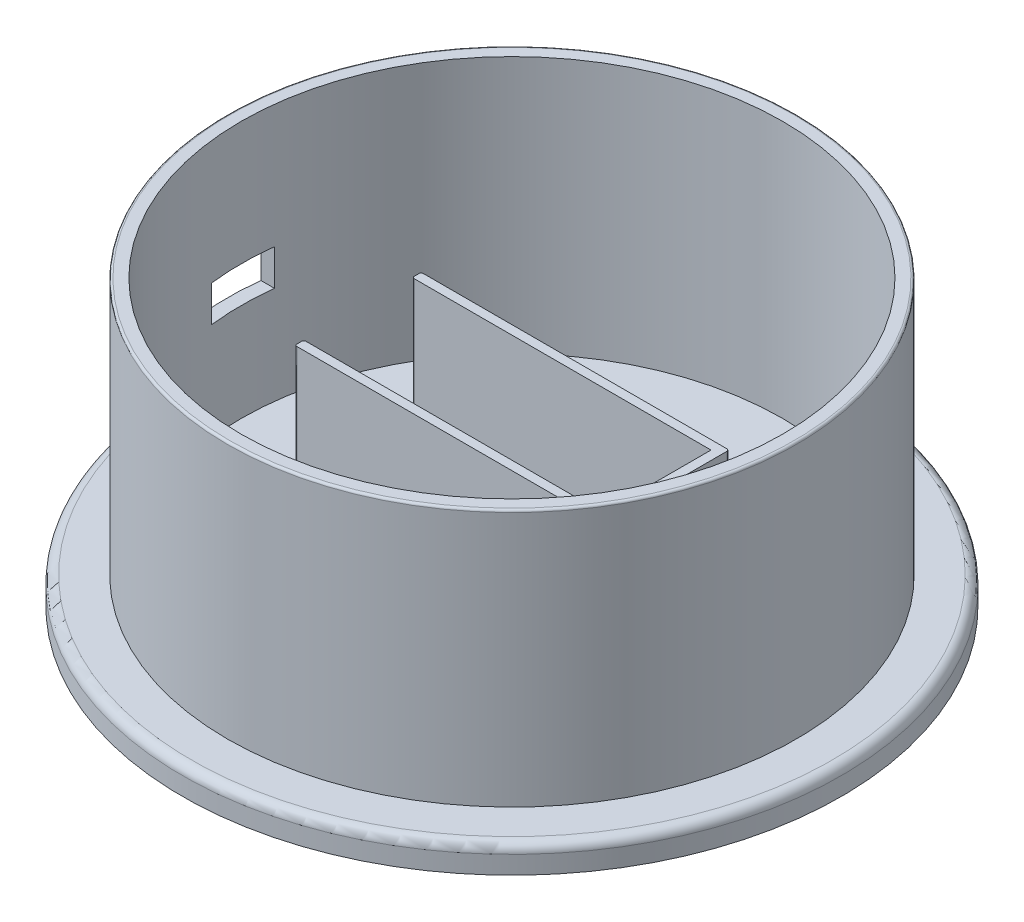
SolidWorks part; units mm, degrees
ref_plane "Front Plane" through (0, 0, 0) normal (0, 0, 1) x (1, 0, 0)
ref_plane "Top Plane" through (0, 0, 0) normal (0, 1, 0) x (1, 0, 0)
ref_plane "Right Plane" through (0, 0, 0) normal (1, 0, 0) x (0, 0, -1)
other "Configuration Table"
sketch "Sketch1" plane through (0, 0, 0) normal (0, 1, 0) x (1, 0, 0)
  circle A0 centre (0, 0) radius 31.5
  circle A1 centre (0, 0) radius 30
  dimension "D1" = 63
  dimension "D2" = 60
extrude "Boss-Extrude1" add sketch "Sketch1" along normal blind 28.5
sketch "Sketch2" plane through (0, 0, 0) normal (0, -1, 0) x (1, 0, 0)
  circle A0 centre (0, 0) radius 36.5
  dimension "D1" = 73
extrude "Boss-Extrude2" add sketch "Sketch2" along normal blind 3
sketch "Sketch3" plane through (0, 0, 0) normal (0, 1, 0) x (1, 0, 0)
  line L0 (-16.05, 6) -> (-17.05, 6)
  line L1 (-16.05, 6) -> (16.05, 6)
  line L3 (-16.05, -6) -> (16.05, -6)
  line L4 (16.05, 6) -> (16.05, -6)
  line L5 (-17.05, 7) -> (17.05, 7)
  line L6 (-17.05, 7) -> (-17.05, 6)
  line L7 (-17.05, -7) -> (17.05, -7)
  line L8 (17.05, 7) -> (17.05, -7)
  line L9 (-16.05, -6) -> (-17.05, -6)
  line L10 (-17.05, -6) -> (-17.05, -7)
  circle A0 centre (0, 0) radius 30 construction
  dimension "D1" = 32.1
  dimension "D4" = 1
  dimension "D2" = 12
  dimension "D3" = 16.05
  dimension "D5" = 1
  dimension "D7" = 1
extrude "Boss-Extrude3" add sketch "Sketch3" along normal blind 17
sketch "Sketch4" plane through (16.05, 0, 0) normal (-1, 0, 0) x (0, 0, 1)
  line L0 (6, 17) -> (6, 0) construction
  line L1 (-3.5, 14.8357) -> (3.5, 14.8357)
  line L2 (-3.5, 14.8357) -> (-3.5, 10.8357)
  line L3 (-3.5, 10.8357) -> (3.5, 10.8357)
  line L4 (3.5, 14.8357) -> (3.5, 10.8357)
  dimension "D1" = 7
  dimension "D2" = 4
  dimension "D3" = 2.5
extrude "Cut-Extrude1" cut sketch "Sketch4" along normal through all
fillet "Fillet1" radius 1 1 edges at (0, 0, -36.5)
fillet "Fillet2" radius 0.25 1 edges at (0, 28.5, 31.5)
fillet "Fillet3" radius 0.25 6 edges at (-17.05, 8.5, 7) (-17.05, 8.5, 6) (-17.05, 8.5, -6) (-17.05, 8.5, -7) (17.05, 8.5, 7) (17.05, 8.5, -7)
